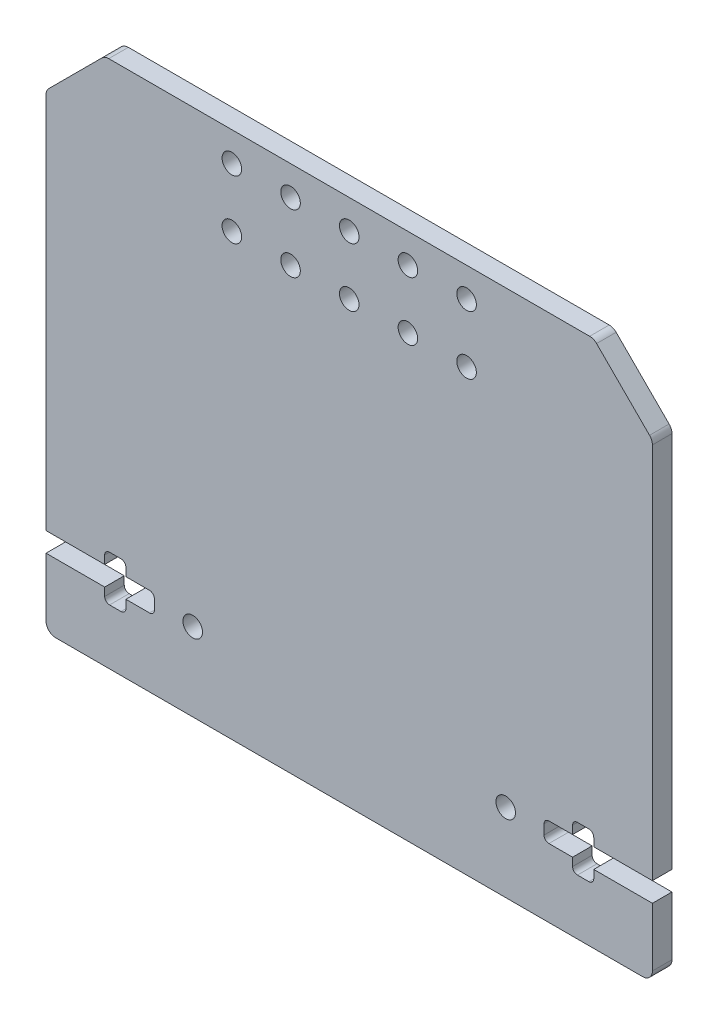
SolidWorks part; units mm, degrees
ref_plane "Alzado" through (0, 0, 0) normal (0, 0, 1) x (1, 0, 0)
ref_plane "Planta" through (0, 0, 0) normal (0, 1, 0) x (1, 0, 0)
ref_plane "Vista lateral" through (0, 0, 0) normal (1, 0, 0) x (0, 0, -1)
sketch "Model" plane through (0, 0, 0) normal (0, 0, 1) x (1, 0, 0)
  line L0 (-1396.3483, 396.9082) -> (-1470.1056, 396.9082)
  line L1 (-1386.7269, 329.4082) -> (-1386.7269, 387.2869)
  line L2 (-1479.7269, 329.4082) -> (-1479.7269, 387.2869)
  line L3 (-1478.2269, 315.9082) -> (-1388.2269, 315.9082)
  line L4 (-1479.7269, 317.4082) -> (-1479.7269, 326.4082)
  line L5 (-1386.7269, 317.4082) -> (-1386.7269, 326.4082)
  line L6 (-1386.7269, 326.4082) -> (-1395.7219, 326.4082)
  line L7 (-1395.7219, 329.4082) -> (-1386.7269, 329.4082)
  line L8 (-1402.5969, 329.4082) -> (-1398.9719, 329.4082)
  line L9 (-1398.9719, 326.4082) -> (-1402.5969, 326.4082)
  line L10 (-1403.3469, 327.1582) -> (-1403.3469, 328.6582)
  line L11 (-1463.8569, 326.4082) -> (-1467.4819, 326.4082)
  line L12 (-1467.4819, 329.4082) -> (-1463.8569, 329.4082)
  line L13 (-1463.1069, 328.6582) -> (-1463.1069, 327.1582)
  line L14 (-1469.9819, 331.4082) -> (-1468.2319, 331.4082)
  line L15 (-1468.2319, 324.4082) -> (-1469.9819, 324.4082)
  line L16 (-1470.7319, 329.4082) -> (-1470.7319, 330.6582)
  line L17 (-1467.4819, 329.4082) -> (-1467.4819, 330.6582)
  line L18 (-1470.7319, 326.4082) -> (-1470.7319, 325.1582)
  line L19 (-1467.4819, 326.4082) -> (-1467.4819, 325.1582)
  line L20 (-1398.2219, 331.4082) -> (-1396.4719, 331.4082)
  line L21 (-1396.4719, 324.4082) -> (-1398.2219, 324.4082)
  line L22 (-1398.9719, 329.4082) -> (-1398.9719, 330.6582)
  line L23 (-1395.7219, 329.4082) -> (-1395.7219, 330.6582)
  line L24 (-1398.9719, 326.4082) -> (-1398.9719, 325.1582)
  line L25 (-1395.7219, 326.4082) -> (-1395.7219, 325.1582)
  line L26 (-1479.7269, 329.4082) -> (-1470.7319, 329.4082)
  line L27 (-1479.7269, 326.4082) -> (-1470.7319, 326.4082)
  line L28 (-1479.2876, 388.3475) -> (-1471.1663, 396.4688)
  line L29 (-1395.2876, 396.4688) -> (-1387.1663, 388.3475)
  circle A0 centre (-1433.2269, 392.4082) radius 1.5
  arc A1 (-1388.2269, 315.9082) -> (-1386.7269, 317.4082) centre (-1388.2269, 317.4082) ccw
  arc A2 (-1479.7269, 317.4082) -> (-1478.2269, 315.9082) centre (-1478.2269, 317.4082) ccw
  circle A3 centre (-1451.2269, 392.4082) radius 1.5
  circle A4 centre (-1442.2269, 392.4082) radius 1.5
  circle A5 centre (-1442.2269, 383.4082) radius 1.5
  circle A6 centre (-1433.2269, 383.4082) radius 1.5
  circle A7 centre (-1451.2269, 383.4082) radius 1.5
  circle A8 centre (-1424.2269, 392.4082) radius 1.5
  circle A9 centre (-1415.2269, 392.4082) radius 1.5
  circle A10 centre (-1424.2269, 383.4082) radius 1.5
  circle A11 centre (-1457.2269, 327.9082) radius 1.5
  circle A12 centre (-1409.2269, 327.9082) radius 1.5
  circle A13 centre (-1415.2269, 383.4082) radius 1.5
  arc A14 (-1463.1069, 328.6582) -> (-1463.8569, 329.4082) centre (-1463.8569, 328.6582) ccw
  arc A15 (-1463.8569, 326.4082) -> (-1463.1069, 327.1582) centre (-1463.8569, 327.1582) ccw
  arc A16 (-1402.5969, 329.4082) -> (-1403.3469, 328.6582) centre (-1402.5969, 328.6582) ccw
  arc A17 (-1403.3469, 327.1582) -> (-1402.5969, 326.4082) centre (-1402.5969, 327.1582) ccw
  arc A18 (-1469.9819, 331.4082) -> (-1470.7319, 330.6582) centre (-1469.9819, 330.6582) ccw
  arc A19 (-1467.4819, 330.6582) -> (-1468.2319, 331.4082) centre (-1468.2319, 330.6582) ccw
  arc A20 (-1468.2319, 324.4082) -> (-1467.4819, 325.1582) centre (-1468.2319, 325.1582) ccw
  arc A21 (-1470.7319, 325.1582) -> (-1469.9819, 324.4082) centre (-1469.9819, 325.1582) ccw
  arc A22 (-1398.2219, 331.4082) -> (-1398.9719, 330.6582) centre (-1398.2219, 330.6582) ccw
  arc A23 (-1395.7219, 330.6582) -> (-1396.4719, 331.4082) centre (-1396.4719, 330.6582) ccw
  arc A24 (-1396.4719, 324.4082) -> (-1395.7219, 325.1582) centre (-1396.4719, 325.1582) ccw
  arc A25 (-1398.9719, 325.1582) -> (-1398.2219, 324.4082) centre (-1398.2219, 325.1582) ccw
  arc A26 (-1479.2876, 388.3475) -> (-1479.7269, 387.2869) centre (-1478.2269, 387.2869) ccw
  arc A27 (-1470.1056, 396.9082) -> (-1471.1663, 396.4688) centre (-1470.1056, 395.4082) ccw
  arc A28 (-1395.2876, 396.4688) -> (-1396.3483, 396.9082) centre (-1396.3483, 395.4082) ccw
  arc A29 (-1386.7269, 387.2869) -> (-1387.1663, 388.3475) centre (-1388.2269, 387.2869) ccw
extrude "Saliente-Extruir1" add sketch "Model" along normal blind 3
